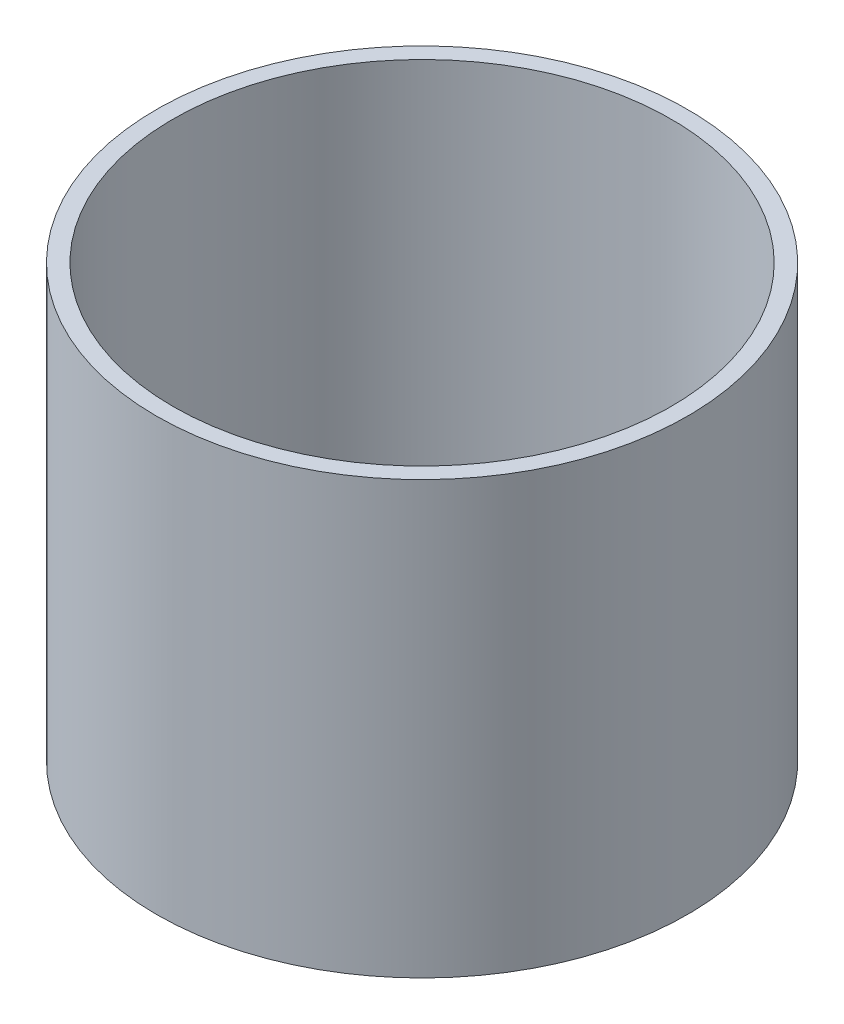
SolidWorks part; units mm, degrees
ref_plane "Front Plane" through (0, 0, 0) normal (0, 0, 1) x (1, 0, 0)
ref_plane "Top Plane" through (0, 0, 0) normal (0, 1, 0) x (1, 0, 0)
ref_plane "Right Plane" through (0, 0, 0) normal (1, 0, 0) x (0, 0, -1)
sketch "Sketch1" plane through (0, 0, 0) normal (0, 1, 0) x (1, 0, 0)
  circle A0 centre (0, 0) radius 37.5
  circle A1 centre (0, 0) radius 40
  dimension "D1" = 75
  dimension "D2" = 80
extrude "Boss-Extrude1" add sketch "Sketch1" along normal blind 65
